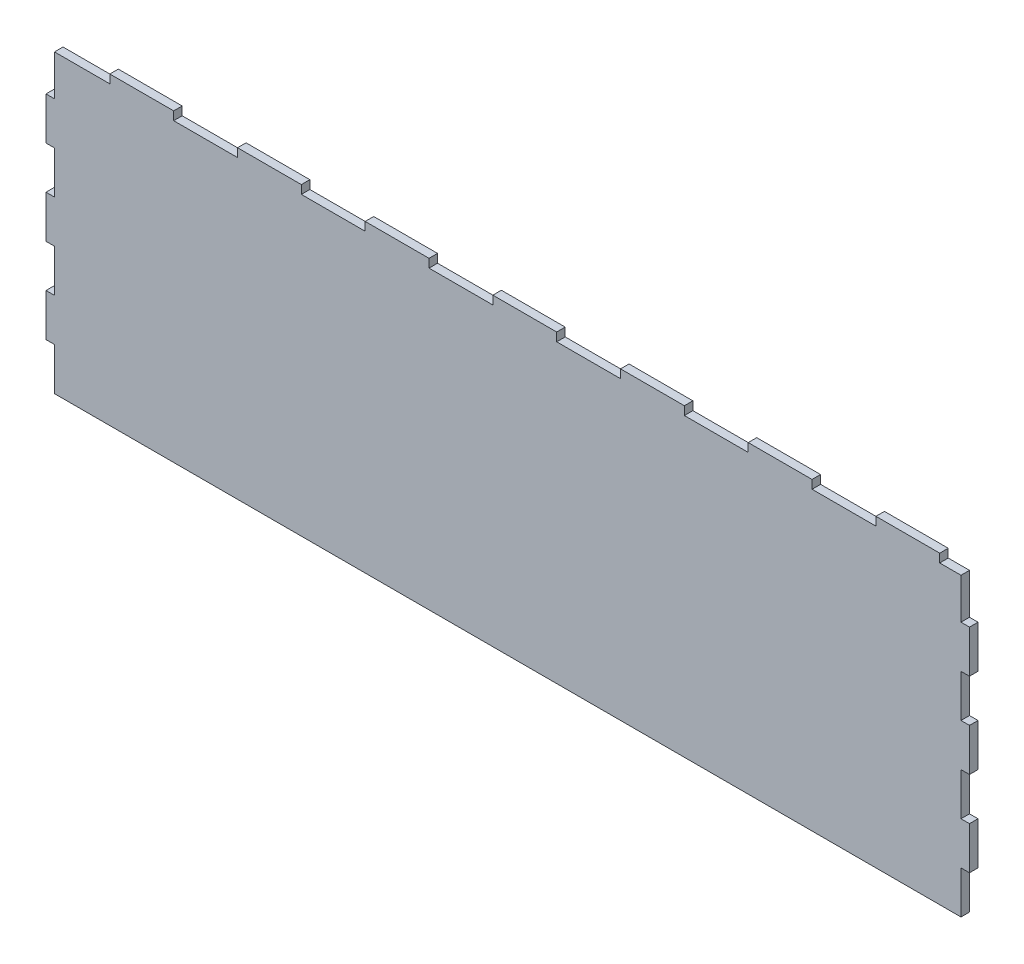
SolidWorks part; units mm, degrees
ref_plane "Front Plane" through (0, 0, 0) normal (0, 0, 1) x (1, 0, 0)
ref_plane "Top Plane" through (0, 0, 0) normal (0, 1, 0) x (1, 0, 0)
ref_plane "Right Plane" through (0, 0, 0) normal (1, 0, 0) x (0, 0, -1)
sketch "Sketch1" plane through (0, 0, 0) normal (0, 0, 1) x (1, 0, 0)
  line L1 (-137.7899, 45.4342) -> (137.7899, 45.4342)
  line L2 (-137.7899, 45.4342) -> (-137.7899, -45.4343)
  line L3 (-137.7899, -45.4343) -> (137.7899, -45.4343)
  line L4 (137.7899, 45.4342) -> (137.7899, -45.4343)
  line L5 (-137.7899, 45.4342) -> (137.7899, -45.4343) construction
  line L6 (-137.7899, -45.4343) -> (137.7899, 45.4342) construction
  point P0 (0, 0)
  dimension "D1" = 275.5798
  dimension "D2" = 90.8685
extrude "Boss-Extrude1" add sketch "Sketch1" along normal blind 2.54
sketch "Sketch2" plane through (0, 0, 2.54) normal (0, 0, 1) x (1, 0, 0)
  line L1 (137.7899, -45.4343) -> (135.2499, -45.4343)
  line L2 (137.7899, -45.4343) -> (137.7899, -32.7343)
  line L3 (137.7899, -32.7343) -> (135.2499, -32.7343)
  line L4 (135.2499, -45.4343) -> (135.2499, -32.7343)
  dimension "D1" = 12.7
  dimension "D2" = 2.54
extrude "Cut-Extrude1" cut sketch "Sketch2" against normal through all
pattern_linear "LPattern1" count 4 spacing 25.4 along (0, 1, 0) of "Cut-Extrude1"
mirror "Mirror1" about plane through (0, 0, 0) normal (1, 0, 0) of "LPattern1", "Cut-Extrude1"
sketch "Sketch3" plane through (0, 0, 2.54) normal (0, 0, 1) x (1, 0, 0)
  line L1 (-137.7899, 45.4342) -> (-118.7399, 45.4342)
  line L2 (-137.7899, 45.4342) -> (-137.7899, 42.8942)
  line L3 (-137.7899, 42.8942) -> (-118.7399, 42.8942)
  line L4 (-118.7399, 45.4342) -> (-118.7399, 42.8942)
  dimension "D1" = 19.05
  dimension "D2" = 2.54
extrude "Cut-Extrude2" cut sketch "Sketch3" against normal through all
pattern_linear "LPattern2" count 8 spacing 38.1 along (1, 0, 0) of "Cut-Extrude2"
